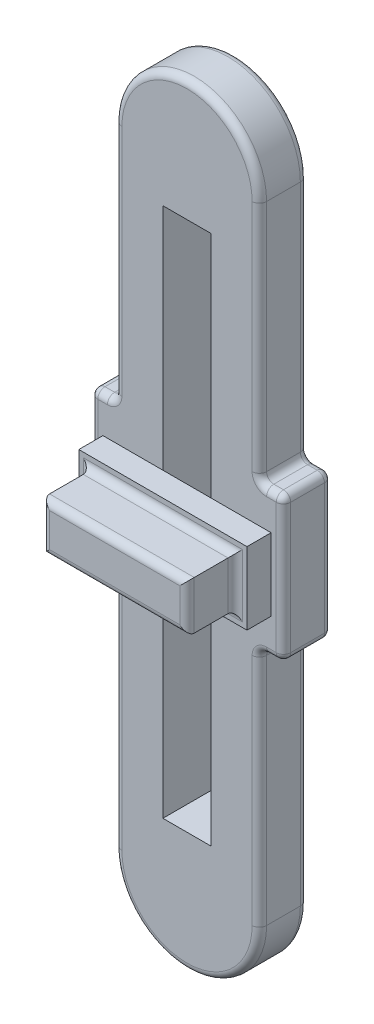
SolidWorks part; units mm, degrees
ref_plane "Front Plane" through (0, 0, 0) normal (0, 0, 1) x (1, 0, 0)
ref_plane "Top Plane" through (0, 0, 0) normal (0, 1, 0) x (1, 0, 0)
ref_plane "Right Plane" through (0, 0, 0) normal (1, 0, 0) x (0, 0, -1)
sketch "Sketch1" plane through (0, 0, 0) normal (0, 0, 1) x (1, 0, 0)
  line L0 (0, 130) -> (0, -130) construction
  line L1 (30, 130) -> (30, 30)
  line L2 (-30, 130) -> (-30, 30)
  line L3 (-30, -30) -> (-30, -130)
  line L4 (-10, 110) -> (10, 110)
  line L5 (-10, 110) -> (-10, -110)
  line L6 (-10, -110) -> (10, -110)
  line L7 (10, 110) -> (10, -110)
  line L8 (-10, 110) -> (10, -110) construction
  line L9 (-10, -110) -> (10, 110) construction
  line L10 (-30, 30) -> (-40, 30)
  line L12 (-30, -30) -> (-40, -30)
  line L13 (-40, 30) -> (-40, -30)
  line L14 (30, 30) -> (40, 30)
  line L16 (30, -30) -> (40, -30)
  line L17 (40, 30) -> (40, -30)
  line L18 (30, -30) -> (30, -130)
  arc A0 (30, 130) -> (-30, 130) centre (0, 130) ccw
  arc A1 (-30, -130) -> (30, -130) centre (0, -130) ccw
  point P2 (0, 0)
  point P8 (0, 0)
  point P21 (-40, 0)
  dimension "D1" = 30
  dimension "D2" = 260
  dimension "D3" = 10
  dimension "D4" = 10
  dimension "D5" = 30
  dimension "D6" = 110
  dimension "D7" = 20
extrude "Boss-Extrude1" add sketch "Sketch1" along normal mid plane 20
sketch "Sketch2" plane through (0, 0, 10) normal (0, 0, 1) x (1, 0, 0)
  line L1 (-30, 10) -> (30, 10)
  line L2 (-30, 10) -> (-30, -10)
  line L3 (-30, -10) -> (30, -10)
  line L4 (30, 10) -> (30, -10)
  line L5 (-30, 10) -> (30, -10) construction
  line L6 (-30, -10) -> (30, 10) construction
  point P0 (0, 0)
  dimension "D1" = 20
  dimension "D2" = 60
extrude "Boss-Extrude2" add sketch "Sketch2" along normal blind 30
sketch "Sketch3" plane through (0, 0, 10) normal (0, 0, 1) x (1, 0, 0)
  line L1 (-30, -10) -> (30, -10)
  line L2 (-30, -10) -> (-30, 10)
  line L3 (-30, 10) -> (30, 10)
  line L4 (30, -10) -> (30, 10)
  line L5 (-30, -10) -> (30, 10) construction
  line L6 (-30, 10) -> (30, -10) construction
  line L7 (-34.8694, -15) -> (34.8694, -15)
  line L8 (-34.8694, -15) -> (-34.8694, 15)
  line L9 (-34.8694, 15) -> (34.8694, 15)
  line L10 (34.8694, -15) -> (34.8694, 15)
  line L11 (-34.8694, -15) -> (34.8694, 15) construction
  line L12 (-34.8694, 15) -> (34.8694, -15) construction
  point P0 (0, 0)
  point P7 (0, 0)
  dimension "D1" = 5
extrude "Boss-Extrude3" add sketch "Sketch3" along normal blind 10
fillet "Fillet2" radius 3 40 edges at (-30, -80, 10) (30, -80, 10) (-30, -80, -10) (30, -80, -10) (30, 80, 10) (-30, 80, 10) (30, 80, -10) (-30, 80, -10) (0, -10, 40) (-30, 0, 40) (0, 10, 40) (30, 0, 40) (30, -30, 0) (35, -30, 10) (35, -30, -10) (35, 30, 10) (30, 30, 0) (35, 30, -10) (-35, -30, 10) (-30, -30, 0) (-35, -30, -10) (-30, 30, 0) (-35, 30, 10) (-35, 30, -10) (-40, 30, 0) (-40, 0, 10) (-40, -30, 0) (-40, 0, -10) (40, -30, 0) (40, 0, 10) (40, 30, 0) (40, 0, -10) (0, -160, 10) (0, -160, -10) (0, 160, 10) (0, 160, -10) (0, 10, 20) (-30, 0, 20) (0, -10, 20) (30, 0, 20)
